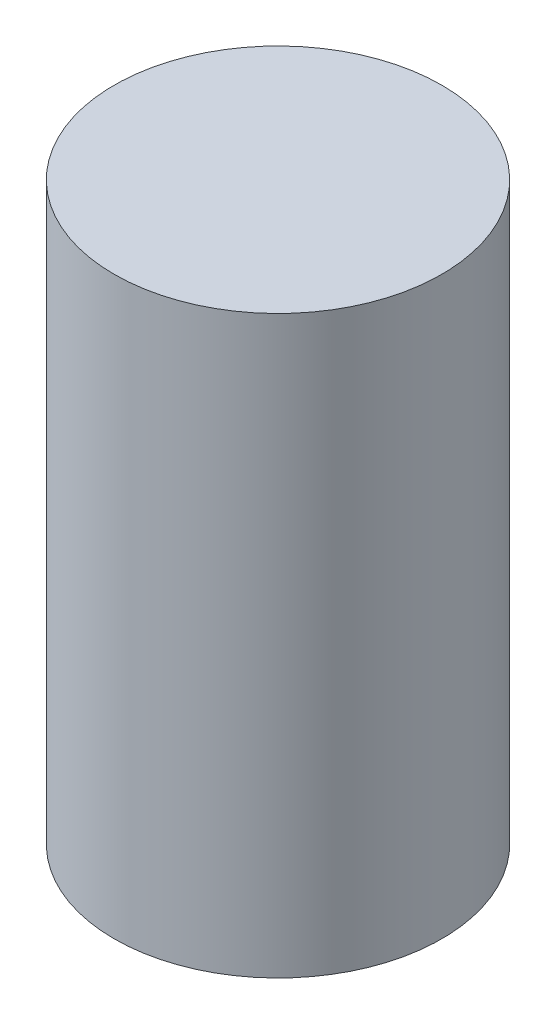
SolidWorks part; units mm, degrees
ref_plane "Front Plane" through (0, 0, 0) normal (0, 0, 1) x (1, 0, 0)
ref_plane "Top Plane" through (0, 0, 0) normal (0, 1, 0) x (1, 0, 0)
ref_plane "Right Plane" through (0, 0, 0) normal (1, 0, 0) x (0, 0, -1)
sketch "Sketch1" plane through (0, 0, 0) normal (0, 1, 0) x (1, 0, 0)
  circle A0 centre (0, 0) radius 86.7674
extrude "Boss-Extrude1" add sketch "Sketch1" along normal blind 304.8
sketch "Sketch3" plane through (0, 304.8, 0) normal (0, 1, 0) x (1, 0, 0)
  circle A0 centre (0, 0) radius 105.8999
